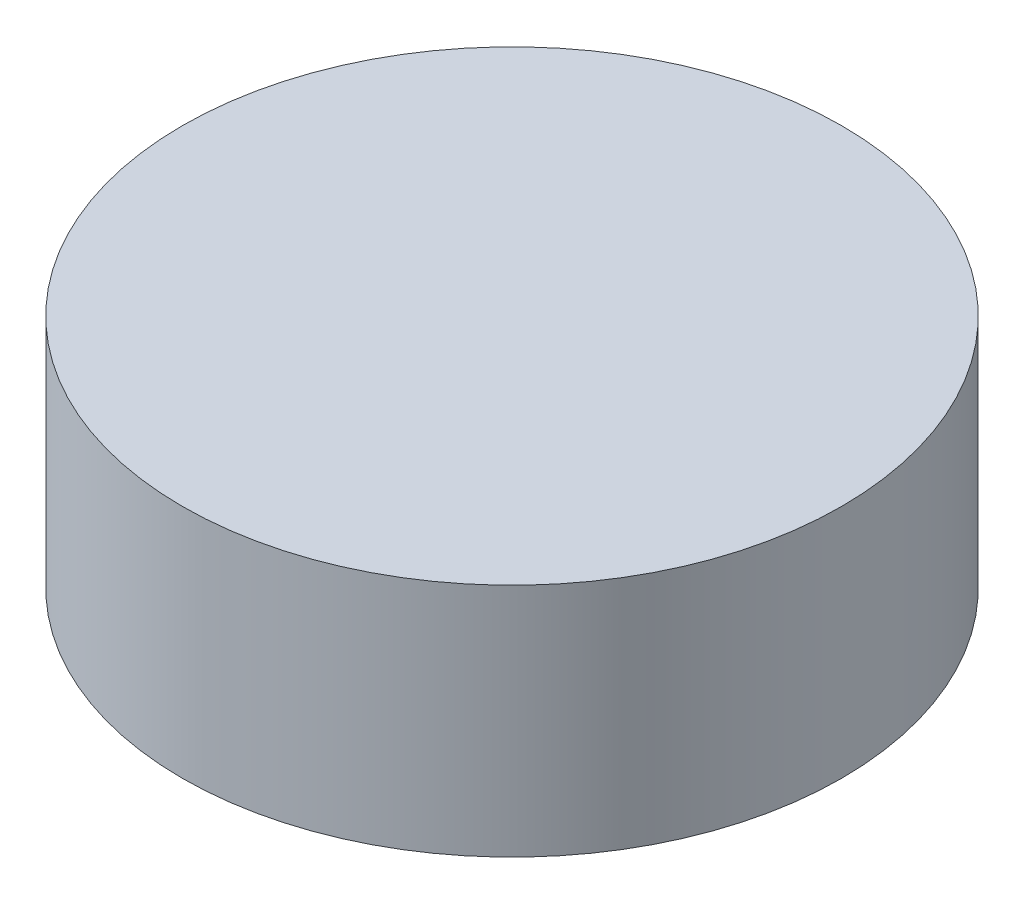
SolidWorks part; units mm, degrees
material "Thornel Mat VMA"
ref_plane "Front Plane" through (0, 0, 0) normal (0, 0, 1) x (1, 0, 0)
ref_plane "Top Plane" through (0, 0, 0) normal (0, 1, 0) x (1, 0, 0)
ref_plane "Right Plane" through (0, 0, 0) normal (1, 0, 0) x (0, 0, -1)
sketch "Sketch1" plane through (0, 0, 0) normal (0, 1, 0) x (1, 0, 0)
  circle A0 centre (0, 0) radius 28
  dimension "D1" = 56
extrude "Boss-Extrude1" add sketch "Sketch1" along normal blind 20
scale "Scale1" scale about centroid uniform scaling yes scale factor 0.650079
